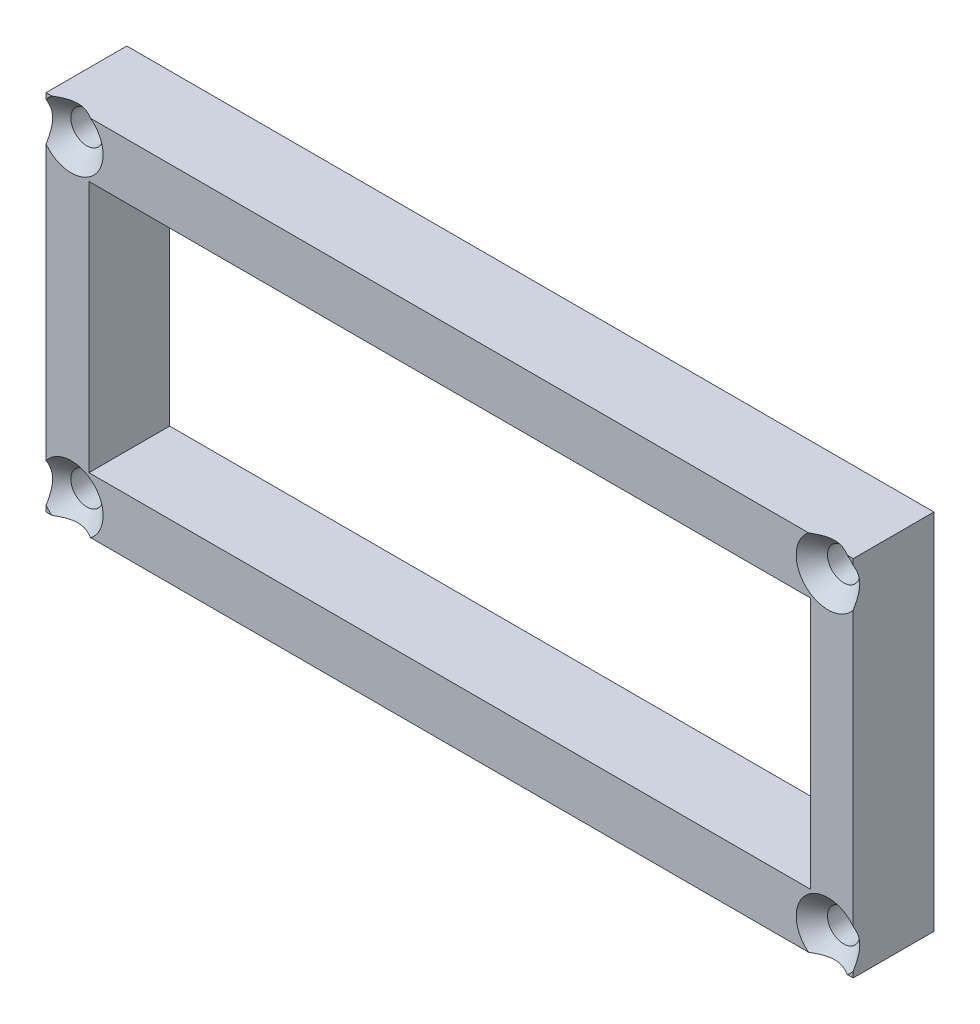
SolidWorks part; units mm, degrees
ref_plane "Front Plane" through (0, 0, 0) normal (0, 0, 1) x (1, 0, 0)
ref_plane "Top Plane" through (0, 0, 0) normal (0, 1, 0) x (1, 0, 0)
ref_plane "Right Plane" through (0, 0, 0) normal (1, 0, 0) x (0, 0, -1)
sketch "Sketch2" plane through (0, 0, 0) normal (0, 0, 1) x (1, 0, 0)
  line L1 (-40, -18) -> (40, -18)
  line L2 (-40, -18) -> (-40, 18)
  line L3 (-40, 18) -> (40, 18)
  line L4 (40, -18) -> (40, 18)
  line L5 (-40, -18) -> (40, 18) construction
  line L6 (-40, 18) -> (40, -18) construction
  point P0 (0, 0)
  dimension "D1" = 80
  dimension "D2" = 36
extrude "Boss-Extrude2" add sketch "Sketch2" along normal blind 8
sketch "Sketch3" plane through (0, 0, 8) normal (0, 0, 1) x (1, 0, 0)
  line L1 (-35.75, -12.5) -> (35.75, -12.5)
  line L2 (-35.75, -12.5) -> (-35.75, 12.5)
  line L3 (-35.75, 12.5) -> (35.75, 12.5)
  line L4 (35.75, -12.5) -> (35.75, 12.5)
  line L5 (-35.75, -12.5) -> (35.75, 12.5) construction
  line L6 (-35.75, 12.5) -> (35.75, -12.5) construction
  point P0 (0, 0)
  dimension "D1" = 71.5
  dimension "D2" = 25
extrude "Cut-Extrude1" cut sketch "Sketch3" against normal blind 8
sketch "Sketch4" plane through (0, 0, 8) normal (0, 0, 1) x (1, 0, 0)
  line L1 (-37.5, -15.5) -> (37.5, -15.5)
  line L2 (-37.5, -15.5) -> (-37.5, 15.5)
  line L3 (-37.5, 15.5) -> (37.5, 15.5)
  line L4 (37.5, -15.5) -> (37.5, 15.5)
  line L5 (-37.5, -15.5) -> (37.5, 15.5) construction
  line L6 (-37.5, 15.5) -> (37.5, -15.5) construction
  point P0 (0, 0)
  dimension "D1" = 75
  dimension "D2" = 31
hole_wizard "CSK for M3 Flat Head Machine Screw1" positions "Sketch5" profile "Sketch6" countersink size "M3" standard "ANSI Metric" end condition through all
sketch "Sketch5" plane through (0, 0, 8) normal (0, 0, 1) x (1, 0, 0)
  point P0 (-37.5, 15.5)
  point P3 (-37.5, -15.5)
  point P6 (37.5, 15.5)
  point P9 (37.5, -15.5)
sketch "Sketch6" plane through (-37.5, 15.5, 8) normal (1, 0, 0) x (0, -1, 0)
  line L0 (0, 0) -> (0, 8)
  line L1 (0, 8) -> (1.6, 8)
  line L2 (1.6, 8) -> (1.6, 1.55)
  line L3 (1.6, 1.55) -> (3.15, 0)
  line L5 (3.15, 0) -> (0, 0)
  line L6 (-1.6, 1.55) -> (-3.15, 0) construction
  line L11 (0, -6.35) -> (0, 107.95) construction
  dimension "Thru Hole Dia." = 3.2
  dimension "Thru Hole Depth" = 8
  dimension "Near C'Sink Dia." = 6.3
  dimension "Near C'Sink Angle" = 90
sketch "Sketch7" plane through (0, 0, 0) normal (0, 0, -1) x (-1, 0, 0)
  line L0 (-35.75, 8.5) -> (-39.75, 6.5)
  line L1 (-35.75, -12.5) -> (-35.75, 12.5) construction
  line L2 (-39.75, 6.5) -> (-39.75, -6.5)
  line L3 (-39.75, -6.5) -> (-35.75, -8.5)
  line L4 (-40, 18) -> (40, 18) construction
  line M6 (-35.75, -12.5) -> (-35.75, 12.5)
  dimension "D1" = 13
  dimension "D2" = 17
  dimension "D3" = 9.5
  dimension "D4" = 4
  dimension "D5" = 2
extrude "Cut-Extrude2" cut sketch "Sketch7" against normal blind 3.5 and the other way through all contours L2 L3 L0 M6
